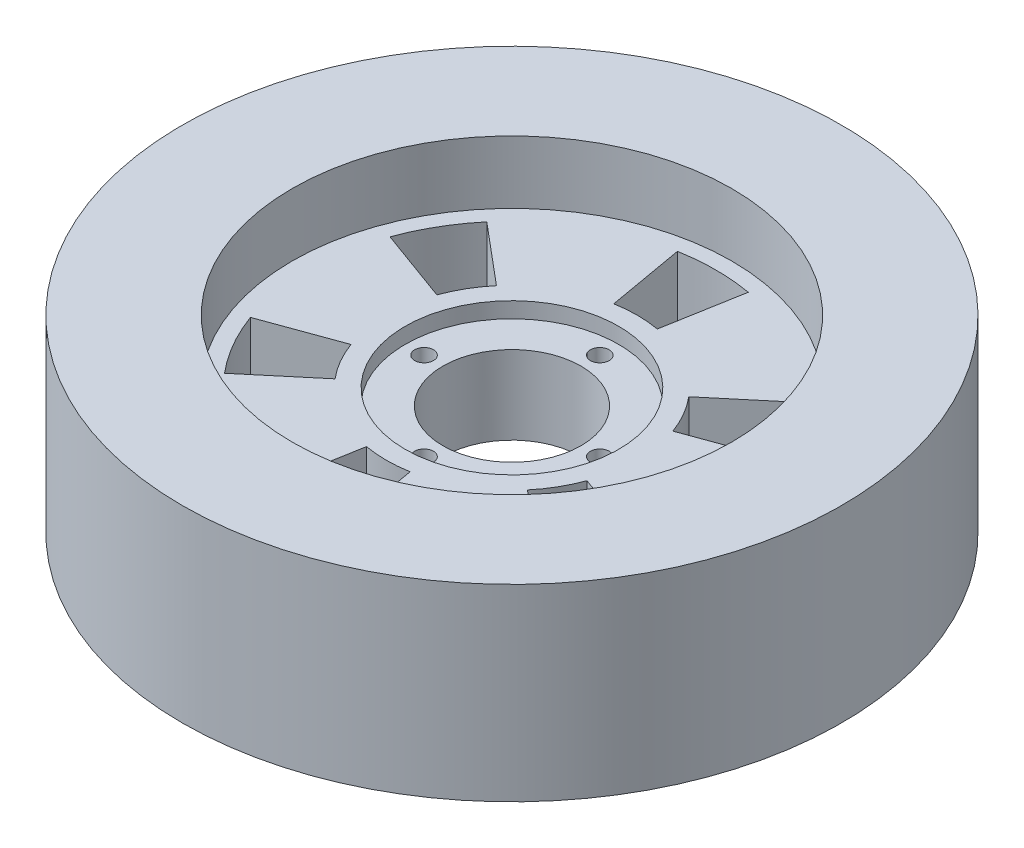
SolidWorks part; units mm, degrees
material "合金钢 (SS)"
ref_plane "前视基准面" through (0, 0, 0) normal (0, 0, 1) x (1, 0, 0)
ref_plane "上视基准面" through (0, 0, 0) normal (0, 1, 0) x (1, 0, 0)
ref_plane "右视基准面" through (0, 0, 0) normal (1, 0, 0) x (0, 0, -1)
sketch "草图1" plane through (0, 0, 0) normal (0, 1, 0) x (1, 0, 0)
  circle A0 centre (0, 0) radius 70
extrude "凸台-拉伸1" add sketch "草图1" along normal mid plane 20
sketch "草图3" plane through (0, 0, 0) normal (0, 1, 0) x (1, 0, 0)
  circle A0 centre (0, 0) radius 105
  circle A1 centre (0, 0) radius 70
extrude "凸台-拉伸3" add sketch "草图3" along normal mid plane 60
sketch "草图6" plane through (0, -10, 0) normal (0, -1, 0) x (1, 0, 0)
  circle A0 centre (0, 0) radius 34
extrude "凸台-拉伸4" add sketch "草图6" along normal blind 10
sketch "草图7" plane through (0, -20, 0) normal (0, -1, 0) x (1, 0, 0)
  circle A12 centre (0, 0) radius 22
extrude "切除-拉伸1" cut sketch "草图7" against normal blind 30
sketch "草图8" plane through (0, -10, 0) normal (0, -1, 0) x (1, 0, 0)
  line L2 (-6.9459, 39.3923) -> (-11.2871, 64.0125)
  line L3 (6.9459, 39.3923) -> (11.2871, 64.0125)
  arc A2 (6.9459, 39.3923) -> (-6.9459, 39.3923) centre (0, 0) ccw
  arc A4 (11.2871, 64.0125) -> (-11.2871, 64.0125) centre (0, 0) ccw
extrude "切除-拉伸2" cut sketch "草图8" against normal blind 20
pattern_circular "阵列(圆周)1" count 6 over 360 about axis through (0, 0, 0) along (0, 1, 0) of "切除-拉伸2"
sketch "草图10" plane through (0, 10, 0) normal (0, 1, 0) x (1, 0, 0)
  circle A0 centre (0, 28) radius 3
  point P2 (0, 0)
extrude "切除-拉伸4" cut sketch "草图10" against normal blind 30
pattern_circular "阵列(圆周)2" count 4 over 360 about axis through (0, 0, 0) along (0, 1, 0) of "切除-拉伸4"
sketch "草图15" plane through (0, 10, 0) normal (0, 1, 0) x (1, 0, 0)
  circle A0 centre (0, 0) radius 34
extrude "切除-拉伸6" cut sketch "草图15" against normal blind 5
